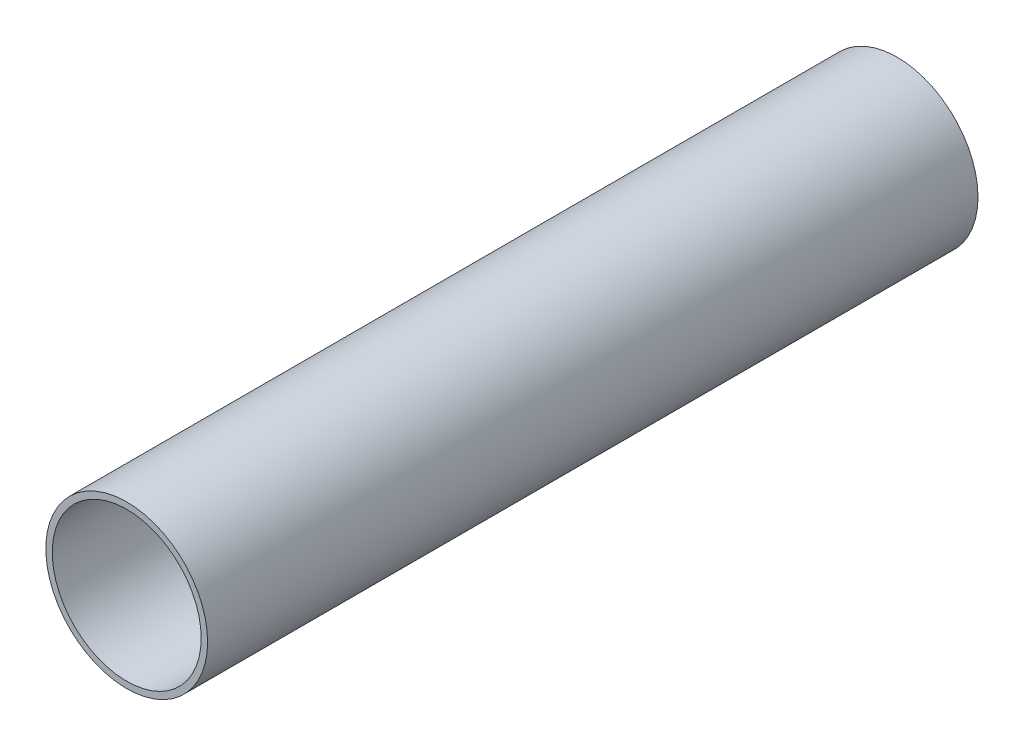
SolidWorks part; units mm, degrees
ref_plane "Plan de face" through (0, 0, 0) normal (0, 0, 1) x (1, 0, 0)
ref_plane "Plan de dessus" through (0, 0, 0) normal (0, 1, 0) x (1, 0, 0)
ref_plane "Plan de droite" through (0, 0, 0) normal (1, 0, 0) x (0, 0, -1)
sketch "Esquisse1" plane through (0, 0, 0) normal (0, 0, 1) x (1, 0, 0)
  circle A0 centre (0, 0) radius 29
  circle A1 centre (0, 0) radius 31.5
  dimension "D1" = 63
  dimension "D2" = 58
extrude "Boss.-Extru.1" add sketch "Esquisse1" along normal blind 300
